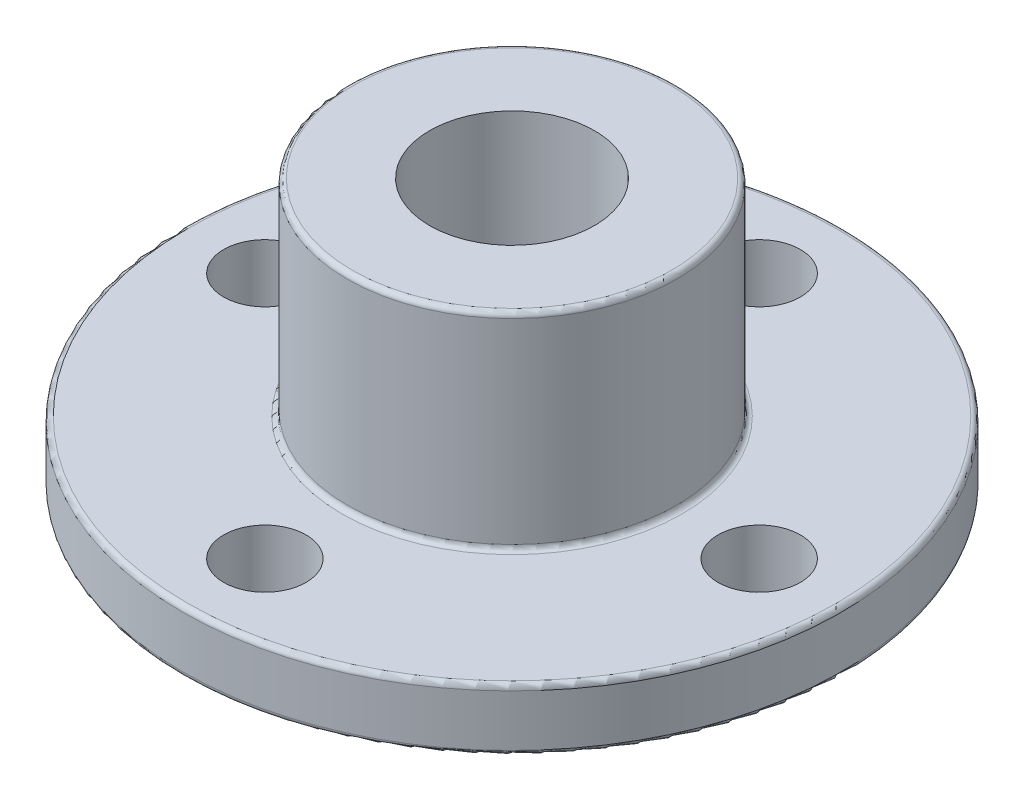
SolidWorks part; units mm, degrees
ref_plane "Front Plane" through (0, 0, 0) normal (0, 0, 1) x (1, 0, 0)
ref_plane "Top Plane" through (0, 0, 0) normal (0, 1, 0) x (1, 0, 0)
ref_plane "Right Plane" through (0, 0, 0) normal (1, 0, 0) x (0, 0, -1)
sketch "Sketch1" plane through (0, 0, 0) normal (0, 1, 0) x (1, 0, 0)
  circle A0 centre (0, 0) radius 16
  dimension "D1" = 32
extrude "Boss-Extrude1" add sketch "Sketch1" along normal blind 3
fillet "Fillet1" radius 0.25 2 edges at (0, 0, 16) (0, 3, 16)
sketch "Sketch2" plane through (0, 3, 0) normal (0, 1, 0) x (1, 0, 0)
  circle A0 centre (0, 0) radius 8
  dimension "D1" = 16
extrude "Boss-Extrude2" add sketch "Sketch2" along normal blind 10
fillet "Fillet2" radius 0.25 2 edges at (0, 3, 8) (0, 13, 8)
sketch "Sketch3" plane through (0, 13, 0) normal (0, 1, 0) x (1, 0, 0)
  circle A0 centre (0, 0) radius 4
  dimension "D1" = 8
extrude "Cut-Extrude1" cut sketch "Sketch3" against normal up to next
sketch "Sketch4" plane through (0, 3, 0) normal (0, 1, 0) x (1, 0, 0)
  circle A0 centre (0, 0) radius 12 construction
  circle A1 centre (0, 12) radius 2
  circle A2 centre (-12, 0) radius 2
  circle A3 centre (0, -12) radius 2
  circle A4 centre (12, 0) radius 2
  dimension "D1" = 24
  dimension "D2" = 4
  dimension "D3" = 4
  dimension "D4" = 4
  dimension "D5" = 4
extrude "Cut-Extrude2" cut sketch "Sketch4" against normal up to next
